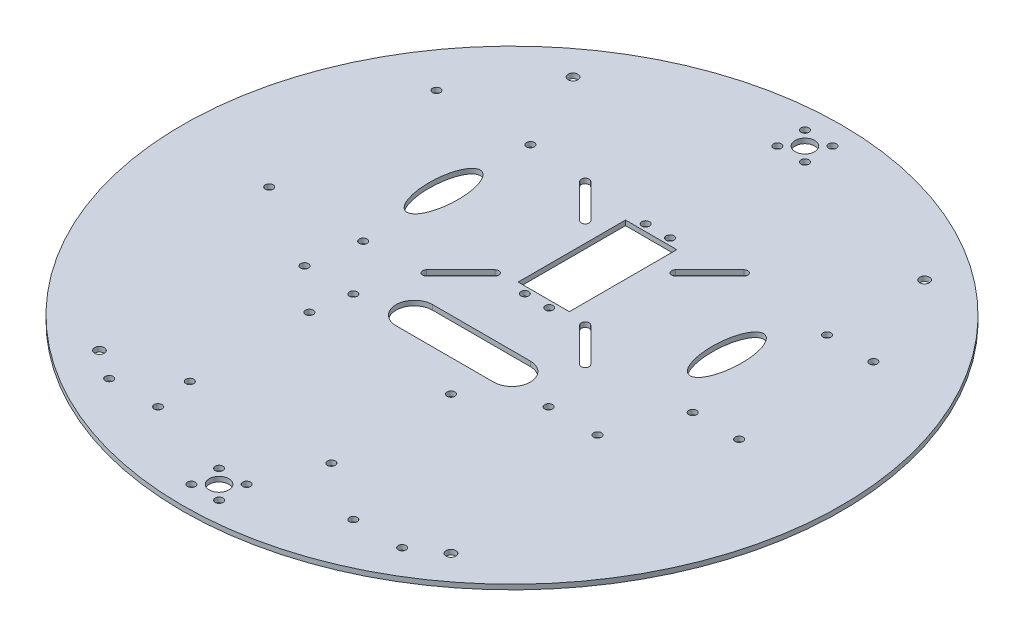
SolidWorks part; units mm, degrees
ref_plane "前视基准面" through (0, 0, 0) normal (0, 0, 1) x (1, 0, 0)
ref_plane "上视基准面" through (0, 0, 0) normal (0, 1, 0) x (1, 0, 0)
ref_plane "右视基准面" through (0, 0, 0) normal (1, 0, 0) x (0, 0, -1)
sketch "草图1" plane through (0, 0, 0) normal (0, 1, 0) x (1, 0, 0)
  line L0 (0, 135) -> (0, -135) construction
  line L1 (-80, 80) -> (80, 80) construction
  line L2 (-80, 80) -> (-80, -80) construction
  line L3 (-80, -80) -> (80, -80) construction
  line L4 (80, 80) -> (80, -80) construction
  line L5 (-80, 80) -> (80, -80) construction
  line L6 (-80, -80) -> (80, 80) construction
  line L7 (-135, 0) -> (135, 0) construction
  line L9 (-30, 60) -> (30, 60) construction
  line L10 (-30, 60) -> (-30, 0) construction
  line L11 (-30, 0) -> (30, 0) construction
  line L12 (30, 60) -> (30, 0) construction
  line L13 (-30, 60) -> (30, 0) construction
  line L14 (-30, 0) -> (30, 60) construction
  circle A0 centre (0, 0) radius 135
  point P17 (0, 0)
  point P19 (0, 30)
  dimension "D1" = 270
  dimension "D2" = 160
  dimension "D3" = 160
  dimension "D5" = 30
  dimension "D6" = 60
  dimension "D7" = 60
extrude "凸台-拉伸1" add sketch "草图1" along normal blind 2
sketch "云台安装孔" plane through (0, 2, 0) normal (0, 1, 0) x (1, 0, 0)
  line L0 (0, 135) -> (0, -135) construction
  line L1 (-135, 0) -> (135, 0) construction
  line L3 (-18.5, 48.5) -> (18.5, 48.5) construction
  line L4 (-18.5, 48.5) -> (-18.5, 11.5) construction
  line L5 (-18.5, 11.5) -> (18.5, 11.5) construction
  line L6 (18.5, 48.5) -> (18.5, 11.5) construction
  line L7 (-18.5, 48.5) -> (18.5, 11.5) construction
  line L8 (-18.5, 11.5) -> (18.5, 48.5) construction
  line L9 (-62.9961, -18.6558) -> (62.9961, -18.6558) construction
  line L10 (-62.9961, -18.6558) -> (-62.9961, -86.2012) construction
  line L11 (-62.9961, -86.2012) -> (62.9961, -86.2012) construction
  line L12 (62.9961, -18.6558) -> (62.9961, -86.2012) construction
  line L13 (-62.9961, -18.6558) -> (62.9961, -86.2012) construction
  line L14 (-62.9961, -86.2012) -> (62.9961, -18.6558) construction
  line L15 (-10.5, 57) -> (10.5, 57)
  line L16 (-10.5, 57) -> (-10.5, 13)
  line L17 (-10.5, 13) -> (10.5, 13)
  line L18 (10.5, 57) -> (10.5, 13)
  line L19 (-10.5, 57) -> (10.5, 13) construction
  line L20 (-10.5, 13) -> (10.5, 57) construction
  line L21 (-5, 59.75) -> (5, 59.75) construction
  line L22 (-5, 59.75) -> (-5, 10.25) construction
  line L23 (-5, 10.25) -> (5, 10.25) construction
  line L24 (5, 59.75) -> (5, 10.25) construction
  line L25 (-5, 59.75) -> (5, 10.25) construction
  line L26 (-5, 10.25) -> (5, 59.75) construction
  line L27 (-38.5, 68.5) -> (38.5, 68.5) construction
  line L28 (-38.5, 68.5) -> (-38.5, -8.5) construction
  line L29 (-38.5, -8.5) -> (38.5, -8.5) construction
  line L30 (38.5, 68.5) -> (38.5, -8.5) construction
  line L31 (-38.5, 68.5) -> (38.5, -8.5) construction
  line L32 (-38.5, -8.5) -> (38.5, 68.5) construction
  circle A0 centre (0, 0) radius 135 construction
  circle A1 centre (-5, 59.75) radius 1.6
  circle A2 centre (5, 59.75) radius 1.6
  circle A3 centre (-5, 10.25) radius 1.6
  circle A4 centre (5, 10.25) radius 1.6
  circle A5 centre (18.5, 48.5) radius 1.6
  circle A6 centre (18.5, 11.5) radius 1.6
  circle A7 centre (-18.5, 11.5) radius 1.6
  circle A8 centre (-18.5, 48.5) radius 1.6
  point P3 (0, 30)
  point P8 (0, 30)
  point P13 (0, -52.4285)
  point P18 (0, 35)
  point P23 (0, 35)
  point P50 (0, 30)
  dimension "D3" = 21
  dimension "D8" = 3.2
  dimension "D9" = 3.2
  dimension "D10" = 3.2
  dimension "D11" = 3.2
  dimension "D12" = 3.2
  dimension "D13" = 3.2
  dimension "D1" = 37
  dimension "D2" = 37
  dimension "D4" = 44
  dimension "D5" = 5
  dimension "D6" = 10
  dimension "D7" = 49.5
  dimension "D14" = 30
  dimension "D15" = 77
  dimension "D16" = 77
extrude "切除-拉伸1" cut sketch "云台安装孔" against normal blind 10
sketch "扩展板安装孔" plane through (0, 2, 0) normal (0, 1, 0) x (1, 0, 0)
  line L0 (0, 135) -> (0, -135) construction
  line L1 (15.5, -40.5) -> (15.5, -89.5) construction
  line L2 (-60, -25) -> (60, -25) construction
  line L3 (-60, -25) -> (-60, -105) construction
  line L4 (-60, -105) -> (60, -105) construction
  line L5 (60, -25) -> (60, -105) construction
  line L6 (-60, -25) -> (60, -105) construction
  line L7 (-60, -105) -> (60, -25) construction
  line L8 (-40, -25) -> (40, -25) construction
  line L9 (-40, -25) -> (-40, -105) construction
  line L10 (-40, -105) -> (40, -105) construction
  line L11 (40, -25) -> (40, -105) construction
  line L12 (-40, -25) -> (40, -105) construction
  line L13 (-40, -105) -> (40, -25) construction
  line L14 (-42.5, -40.5) -> (42.5, -40.5) construction
  line L15 (-42.5, -40.5) -> (-42.5, -89.5) construction
  line L16 (-42.5, -89.5) -> (42.5, -89.5) construction
  line L17 (42.5, -40.5) -> (42.5, -89.5) construction
  line L18 (-42.5, -40.5) -> (42.5, -89.5) construction
  line L19 (-42.5, -89.5) -> (42.5, -40.5) construction
  circle A0 centre (0, 0) radius 135 construction
  circle A1 centre (-60, -25) radius 1.6
  circle A2 centre (-40, -25) radius 1.6
  circle A3 centre (40, -25) radius 1.6
  circle A4 centre (60, -25) radius 1.6
  circle A5 centre (60, -105) radius 1.6
  circle A6 centre (40, -105) radius 1.6
  circle A7 centre (-40, -105) radius 1.6
  circle A8 centre (-60, -105) radius 1.6
  circle A9 centre (-42.5, -89.5) radius 1.6
  circle A12 centre (-42.5, -40.5) radius 1.6
  circle A13 centre (15.5, -40.5) radius 1.6
  circle A14 centre (15.5, -89.5) radius 1.6
  point P5 (0, -65)
  point P10 (0, -65)
  point P15 (0, -65)
  dimension "D7" = 65
  dimension "D1" = 120
  dimension "D2" = 80
  dimension "D3" = 80
  dimension "D4" = 85
  dimension "D5" = 49
  dimension "D6" = 58
extrude "切除-拉伸2" cut sketch "扩展板安装孔" against normal blind 10
sketch "草图4" plane through (0, 2, 0) normal (0, 1, 0) x (1, 0, 0)
  line L0 (0, 135) -> (0, -135) construction
  line L1 (-135, 0) -> (135, 0) construction
  line L2 (-20, -12.5) -> (20, -12.5)
  line L3 (-20, -12.5) -> (-20, -27.5) construction
  line L4 (-20, -27.5) -> (20, -27.5)
  line L5 (20, -12.5) -> (20, -27.5) construction
  line L6 (-20, -12.5) -> (20, -27.5) construction
  line L7 (-20, -27.5) -> (20, -12.5) construction
  line L8 (-72, 97) -> (72, 97) construction
  line L9 (-72, 97) -> (-72, -97) construction
  line L10 (-72, -97) -> (72, -97) construction
  line L11 (72, 97) -> (72, -97) construction
  line L12 (-72, 97) -> (72, -97) construction
  line L13 (-72, -97) -> (72, 97) construction
  circle A0 centre (0, 0) radius 135 construction
  arc A1 (-20, -12.5) -> (-20, -27.5) centre (-20, -20) ccw
  arc A2 (20, -12.5) -> (20, -27.5) centre (20, -20) cw
  circle A3 centre (-72, 97) radius 2
  circle A4 centre (72, 97) radius 2
  circle A5 centre (72, -97) radius 2
  circle A6 centre (-72, -97) radius 2
  circle A7 centre (0, -120) radius 4
  circle A8 centre (0, 120) radius 8 construction
  circle A9 centre (-5.6569, -125.6569) radius 1.6
  circle A10 centre (-5.6569, -114.3431) radius 1.6
  circle A11 centre (5.6569, -114.3431) radius 1.6
  circle A12 centre (5.6569, -125.6569) radius 1.6
  circle A13 centre (5.6569, 125.6569) radius 1.6
  circle A14 centre (5.6569, 114.3431) radius 1.6
  circle A15 centre (-5.6569, 114.3431) radius 1.6
  circle A16 centre (-5.6569, 125.6569) radius 1.6
  circle A17 centre (0, -120) radius 8 construction
  circle A18 centre (0, 120) radius 4
  point P5 (0, -20)
  point P12 (0, 0)
  point P41 (0, -120)
  point P50 (0, 120)
  dimension "D5" = 120
  dimension "D6" = 4
  dimension "D7" = 4
  dimension "D8" = 4
  dimension "D9" = 4
  dimension "D12" = 4
  dimension "D10" = 16
  dimension "D11" = 4
  dimension "D1" = 15
  dimension "D2" = 40
  dimension "D3" = 144
  dimension "D4" = 194
  dimension "D13" = 20
extrude "切除-拉伸3" cut sketch "草图4" against normal blind 10
sketch "草图5" plane through (0, 2, 0) normal (0, 1, 0) x (1, 0, 0)
  line L0 (-31.3686, 63.6314) -> (-17.3686, 49.6314)
  line L1 (-10.5, 57) -> (-10.5, 13) construction
  line L2 (-33.6314, 61.3686) -> (-19.6314, 47.3686)
  line L3 (-32.5, 62.5) -> (32.5, 62.5) construction
  line L4 (-32.5, 62.5) -> (-32.5, -2.5) construction
  line L5 (-32.5, -2.5) -> (32.5, -2.5) construction
  line L6 (32.5, 62.5) -> (32.5, -2.5) construction
  line L7 (-32.5, 62.5) -> (32.5, -2.5) construction
  line L8 (-32.5, -2.5) -> (32.5, 62.5) construction
  line L9 (33.6314, 61.3686) -> (19.6314, 47.3686)
  line L10 (31.3686, 63.6314) -> (17.3686, 49.6314)
  line L11 (31.3686, -3.6314) -> (17.3686, 10.3686)
  line L12 (33.6314, -1.3686) -> (19.6314, 12.6314)
  line L13 (-33.6314, -1.3686) -> (-19.6314, 12.6314)
  line L14 (-31.3686, -3.6314) -> (-17.3686, 10.3686)
  arc A0 (33.6314, 61.3686) -> (31.3686, 63.6314) centre (32.5, 62.5) ccw
  arc A1 (-19.6314, 47.3686) -> (-17.3686, 49.6314) centre (-18.5, 48.5) ccw
  arc A2 (-31.3686, 63.6314) -> (-33.6314, 61.3686) centre (-32.5, 62.5) ccw
  arc A3 (17.3686, 49.6314) -> (19.6314, 47.3686) centre (18.5, 48.5) ccw
  arc A4 (31.3686, -3.6314) -> (33.6314, -1.3686) centre (32.5, -2.5) ccw
  arc A5 (19.6314, 12.6314) -> (17.3686, 10.3686) centre (18.5, 11.5) ccw
  arc A6 (-33.6314, -1.3686) -> (-31.3686, -3.6314) centre (-32.5, -2.5) ccw
  arc A7 (-17.3686, 10.3686) -> (-19.6314, 12.6314) centre (-18.5, 11.5) ccw
  point P5 (0, 30)
  point P35 (0, 30)
  dimension "D4" = 3.2
  dimension "D1" = 30
  dimension "D2" = 10.5
  dimension "D3" = 65
  dimension "D5" = 1.6
  dimension "D6" = 4
extrude "切除-拉伸4" cut sketch "草图5" against normal blind 10
sketch "草图6" plane through (0, 2, 0) normal (0, 1, 0) x (1, 0, 0)
  line L0 (33.6314, -3.6314) -> (33.6314, 63.6314) construction
  line L1 (33.6314, 30) -> (118.3005, 30) construction
  line L2 (0, 120) -> (0, -27.5) construction
  line L3 (-20, -27.5) -> (20, -27.5) construction
  line L4 (-33.6314, -3.6314) -> (-33.6314, 63.6314) construction
  line L5 (71.5372, 2.5) -> (90.5372, 2.5) construction
  line L6 (71.5372, 2.5) -> (71.5372, 57.5) construction
  line L7 (71.5372, 57.5) -> (90.5372, 57.5) construction
  line L8 (90.5372, 2.5) -> (90.5372, 57.5) construction
  line L9 (71.5372, 2.5) -> (90.5372, 57.5) construction
  line L10 (71.5372, 57.5) -> (90.5372, 2.5) construction
  line L11 (-33.6314, 30) -> (-118.3005, 30) construction
  line L14 (-95.216, -4.25) -> (-56.716, -4.25) construction
  line L15 (-95.216, -4.25) -> (-95.216, 64.25) construction
  line L16 (-95.216, 64.25) -> (-56.716, 64.25) construction
  line L17 (-56.716, -4.25) -> (-56.716, 64.25) construction
  line L18 (-95.216, -4.25) -> (-56.716, 64.25) construction
  line L19 (-95.216, 64.25) -> (-56.716, -4.25) construction
  arc A0 (31.3686, -3.6314) -> (33.6314, -1.3686) centre (32.5, -2.5) ccw construction
  arc A1 (33.6314, 61.3686) -> (31.3686, 63.6314) centre (32.5, 62.5) ccw construction
  circle A2 centre (71.5372, 2.5) radius 1.6
  circle A3 centre (90.5372, 2.5) radius 1.6
  circle A4 centre (90.5372, 57.5) radius 1.6
  circle A5 centre (71.5372, 57.5) radius 1.6
  circle A6 centre (-95.216, -4.25) radius 1.6
  circle A7 centre (-56.716, -4.25) radius 1.6
  circle A8 centre (-95.216, 64.25) radius 1.6
  circle A9 centre (-56.716, 64.25) radius 1.6
  ellipse E0 centre (-58.0311, 30) end of major axis (-58.0311, 15) minor radius 6
  ellipse E1 centre (58.0311, 30) end of major axis (58.0311, 45) minor radius 6
  point P15 (81.0372, 30)
  point P49 (-75.966, 30)
  dimension "D3" = 6
  dimension "D7" = 3.2
  dimension "D1" = 19
  dimension "D2" = 55
  dimension "D4" = 15
  dimension "D5" = 38.5
  dimension "D6" = 68.5
extrude "切除-拉伸7" cut sketch "草图6" against normal blind 10
